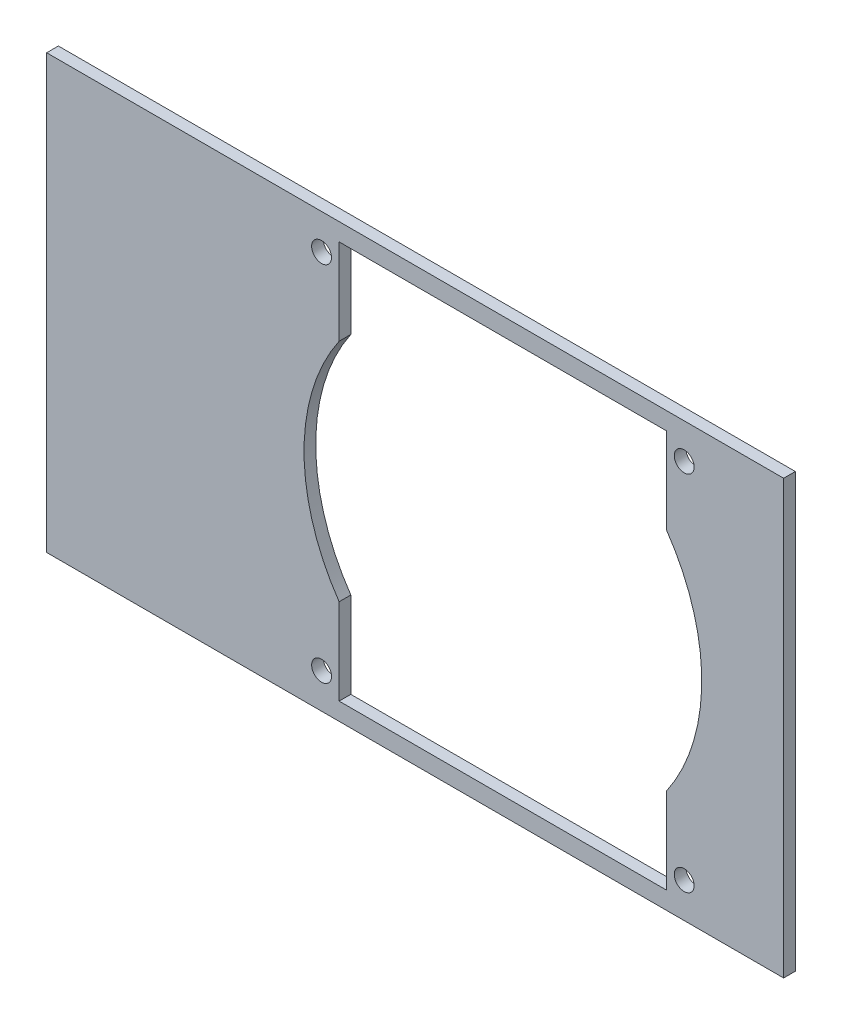
SolidWorks part; units mm, degrees
ref_plane "Plano frontal" through (0, 0, 0) normal (0, 0, 1) x (1, 0, 0)
ref_plane "Plano superior" through (0, 0, 0) normal (0, 1, 0) x (1, 0, 0)
ref_plane "Plano direito" through (0, 0, 0) normal (1, 0, 0) x (0, 0, -1)
sketch "Esboço1" plane through (0, 0, 0) normal (0, 0, 1) x (1, 0, 0)
  line L0 (0, 0) -> (126, 0)
  line L1 (50, -3) -> (50, -17.7127)
  line L2 (126, -74) -> (0, -74)
  line L3 (0, -74) -> (0, 0)
  line L4 (47, -6) -> (109, -6) construction
  line L5 (50, -71) -> (106, -71)
  line L6 (126, 0) -> (126, -74)
  line L7 (50, -56.2873) -> (50, -71)
  line L8 (106, -3) -> (106, -17.7127)
  line L9 (106, -56.2873) -> (106, -71)
  line L10 (47, -6) -> (109, -68) construction
  line L11 (109, -6) -> (109, -68) construction
  line L13 (50, -3) -> (106, -3)
  circle A0 centre (47, -6) radius 1.7
  circle A1 centre (109, -6) radius 1.7
  circle A2 centre (47, -68) radius 1.7
  circle A3 centre (109, -68) radius 1.7
  arc A4 (50, -17.7127) -> (50, -56.2873) centre (78, -37) ccw
  arc A5 (106, -56.2873) -> (106, -17.7127) centre (78, -37) ccw
  point P13 (78, -6)
  point P22 (0, 0)
  point P23 (78, -3)
  dimension "D4" = 3.4
  dimension "D1" = 20
  dimension "D2" = 56
  dimension "D3" = 62
  dimension "D5" = 126
  dimension "D6" = 74
  dimension "D7" = 3
  dimension "D8" = 3
  dimension "D9" = 6
extrude "Ressalto-extrusão1" add sketch "Esboço1" along normal blind 2
